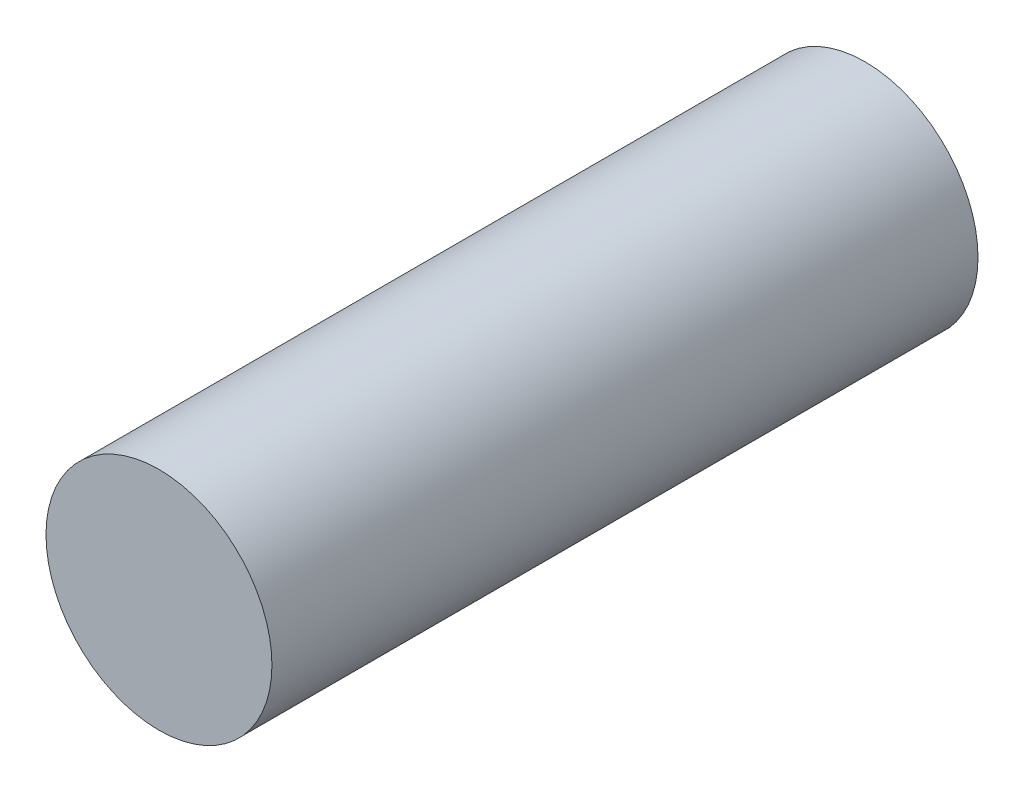
SolidWorks part; units mm, degrees
ref_plane "前视基准面" through (0, 0, 0) normal (0, 0, 1) x (1, 0, 0)
ref_plane "上视基准面" through (0, 0, 0) normal (0, 1, 0) x (1, 0, 0)
ref_plane "右视基准面" through (0, 0, 0) normal (1, 0, 0) x (0, 0, -1)
sketch "草图1" plane through (0, 0, 0) normal (0, 0, 1) x (1, 0, 0)
  circle A0 centre (0, -175) radius 4
  circle A1 centre (0, -175) radius 4 construction
extrude "凸台-拉伸1" add sketch "草图1" along normal mid plane 25
